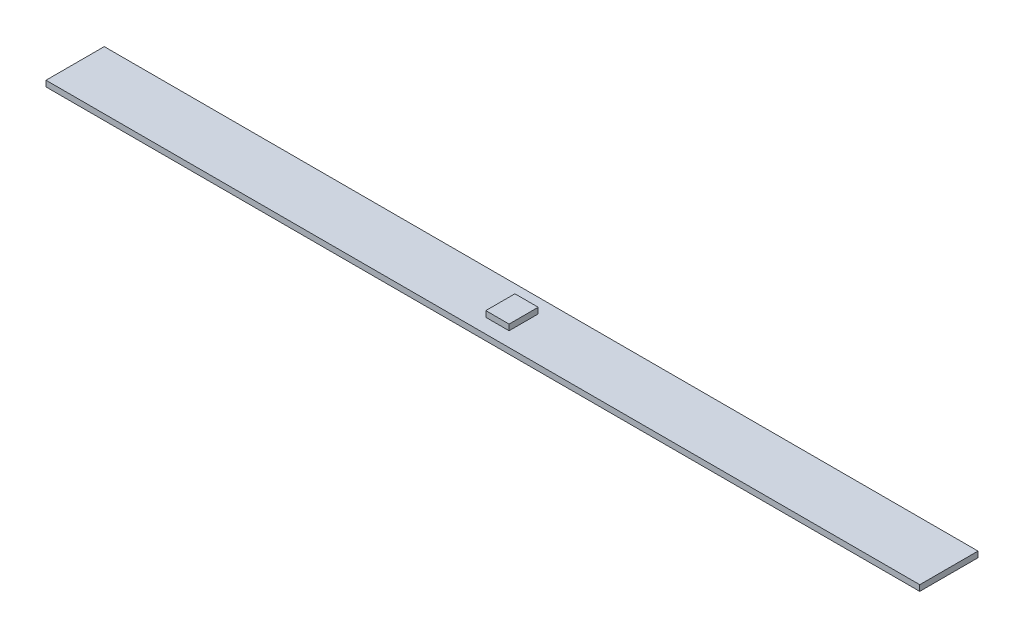
SolidWorks part; units mm, degrees
ref_plane "Front Plane" through (0, 0, 0) normal (0, 0, 1) x (1, 0, 0)
ref_plane "Top Plane" through (0, 0, 0) normal (0, 1, 0) x (1, 0, 0)
ref_plane "Right Plane" through (0, 0, 0) normal (1, 0, 0) x (0, 0, -1)
sketch "Sketch1" plane through (0, 0, 0) normal (0, 1, 0) x (1, 0, 0)
  line L1 (-75, 5) -> (75, 5)
  line L2 (-75, 5) -> (-75, -5)
  line L3 (-75, -5) -> (75, -5)
  line L4 (75, 5) -> (75, -5)
  line L5 (-75, 5) -> (75, -5) construction
  line L6 (-75, -5) -> (75, 5) construction
  point P0 (0, 0)
  dimension "D1" = 10
  dimension "D2" = 150
extrude "Boss-Extrude1" add sketch "Sketch1" along normal blind 1
sketch "Sketch2" plane through (0, 1, 0) normal (0, 1, 0) x (1, 0, 0)
  line L1 (-2, 2.5) -> (2, 2.5)
  line L2 (-2, 2.5) -> (-2, -2.5)
  line L3 (-2, -2.5) -> (2, -2.5)
  line L4 (2, 2.5) -> (2, -2.5)
  line L5 (-2, 2.5) -> (2, -2.5) construction
  line L6 (-2, -2.5) -> (2, 2.5) construction
  point P0 (0, 0)
  dimension "D1" = 4
  dimension "D2" = 5
extrude "Boss-Extrude2" add sketch "Sketch2" along normal blind 1
